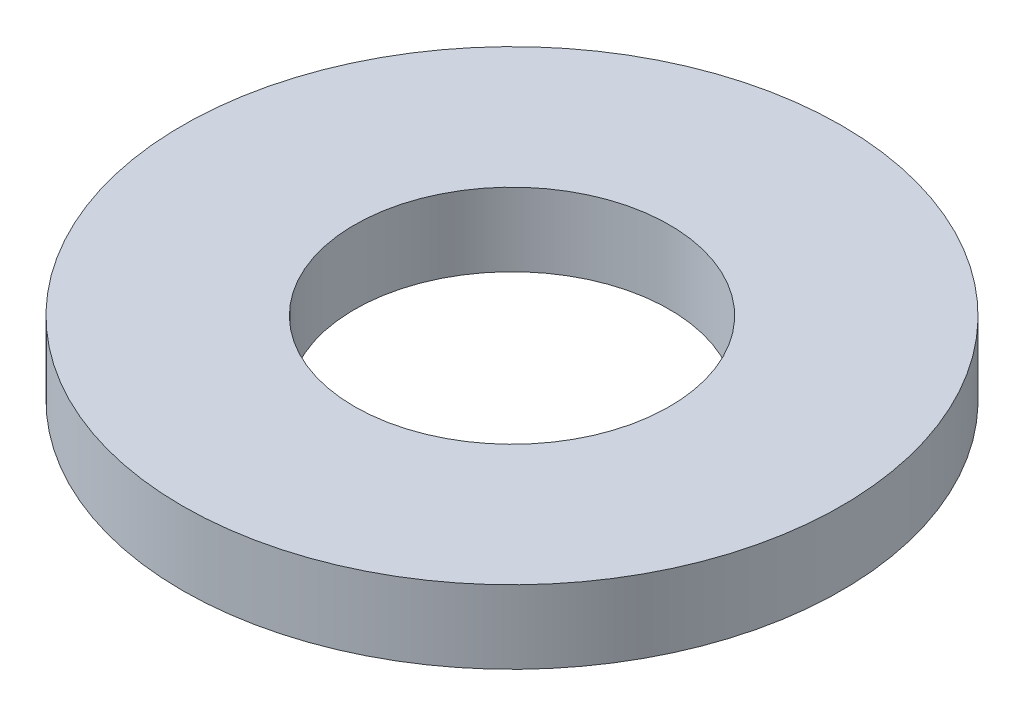
SolidWorks part; units mm, degrees
ref_plane "Front Plane" through (0, 0, 0) normal (0, 0, 1) x (1, 0, 0)
ref_plane "Top Plane" through (0, 0, 0) normal (0, 1, 0) x (1, 0, 0)
ref_plane "Right Plane" through (0, 0, 0) normal (1, 0, 0) x (0, 0, -1)
sketch "Sketch2" plane through (0, 0, 0) normal (0, 1, 0) x (1, 0, 0)
  circle A0 centre (0, 0) radius 4.5
  circle A1 centre (0, 0) radius 2.15
extrude "Boss-Extrude1" add sketch "Sketch2" along normal blind 1
